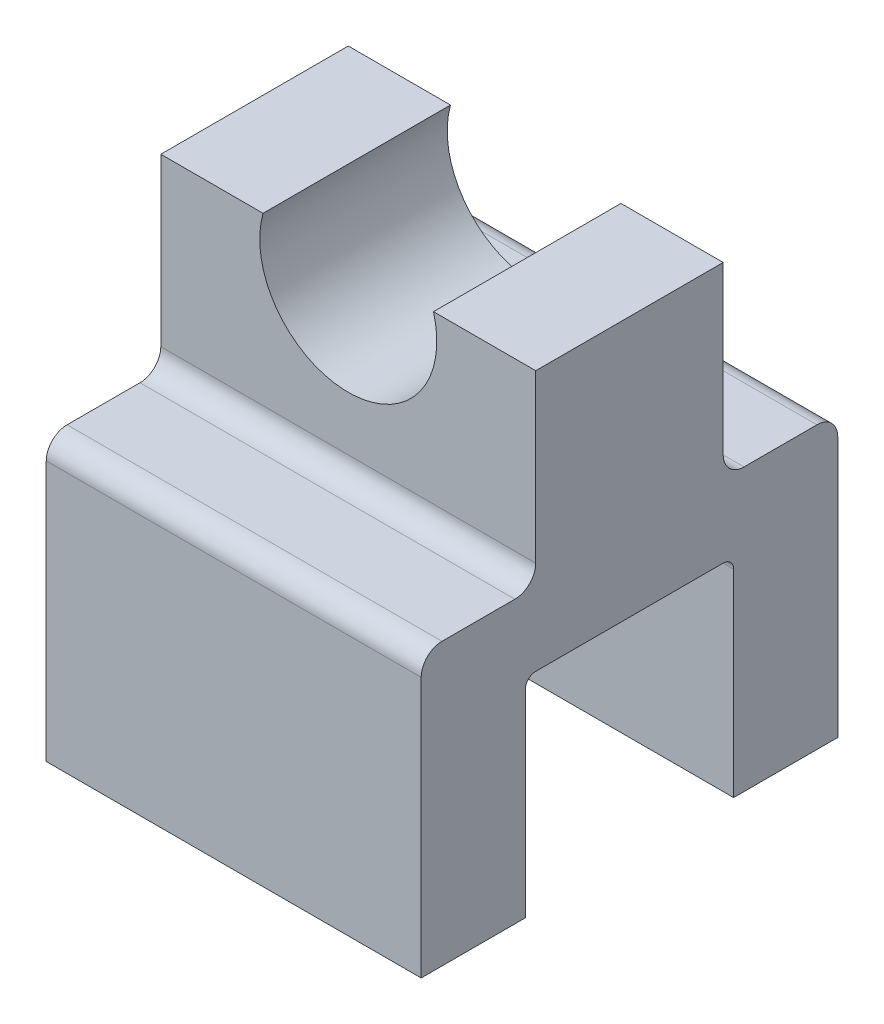
SolidWorks part; units mm, degrees
ref_plane "Front Plane" through (0, 0, 0) normal (0, 0, 1) x (1, 0, 0)
ref_plane "Top Plane" through (0, 0, 0) normal (0, 1, 0) x (1, 0, 0)
ref_plane "Right Plane" through (0, 0, 0) normal (1, 0, 0) x (0, 0, -1)
sketch "Sketch1" plane through (0, 0, 0) normal (0, 0, 1) x (1, 0, 0)
  line L0 (33.2523, 57.15) -> (45.72, 57.15)
  line L1 (0, 0) -> (45.72, 0)
  line L2 (0, 0) -> (0, 57.15)
  line L3 (0, 57.15) -> (12.4677, 57.15)
  line L4 (45.72, 0) -> (45.72, 57.15)
  arc A0 (12.4677, 57.15) -> (33.2523, 57.15) centre (22.86, 54.229) ccw
  dimension "D3" = 21.59
  dimension "D1" = 45.72
  dimension "D2" = 22.86
  dimension "D4" = 54.229
  dimension "D5" = 57.15
extrude "Boss-Extrude1" add sketch "Sketch1" along normal blind 50.8
sketch "Sketch2" plane through (45.72, 0, 0) normal (1, 0, 0) x (0, 0, -1)
  line L0 (-50.8, 0) -> (0, 0) construction
  line L1 (-38.1, 0) -> (-12.7, 0)
  line L2 (-38.1, 0) -> (-38.1, 25.4)
  line L3 (-38.1, 25.4) -> (-12.7, 25.4)
  line L4 (-12.7, 0) -> (-12.7, 25.4)
  line L5 (-50.8, 0) -> (-50.8, 57.15) construction
  dimension "D1" = 25.4
  dimension "D2" = 25.4
  dimension "D3" = 12.7
extrude "Cut-Extrude1" cut sketch "Sketch2" against normal through all
fillet "Fillet1" radius 1.27 2 edges at (22.86, 25.4, 38.1) (22.86, 25.4, 12.7)
sketch "Sketch4" plane through (0, 0, 0) normal (-1, 0, 0) x (0, 0, 1)
  line L1 (50.8, 57.15) -> (36.83, 57.15)
  line L2 (50.8, 57.15) -> (50.8, 34.29)
  line L3 (50.8, 34.29) -> (36.83, 34.29)
  line L4 (36.83, 57.15) -> (36.83, 34.29)
  line L5 (0, 57.15) -> (13.97, 57.15)
  line L6 (0, 57.15) -> (0, 34.29)
  line L7 (0, 34.29) -> (13.97, 34.29)
  line L8 (13.97, 57.15) -> (13.97, 34.29)
  dimension "D1" = 22.86
  dimension "D2" = 22.86
extrude "Cut-Extrude2" cut sketch "Sketch4" against normal through all
fillet "Fillet2" radius 2.54 4 edges at (22.86, 34.29, 0) (22.86, 34.29, 50.8) (22.86, 34.29, 36.83) (22.86, 34.29, 13.97)
